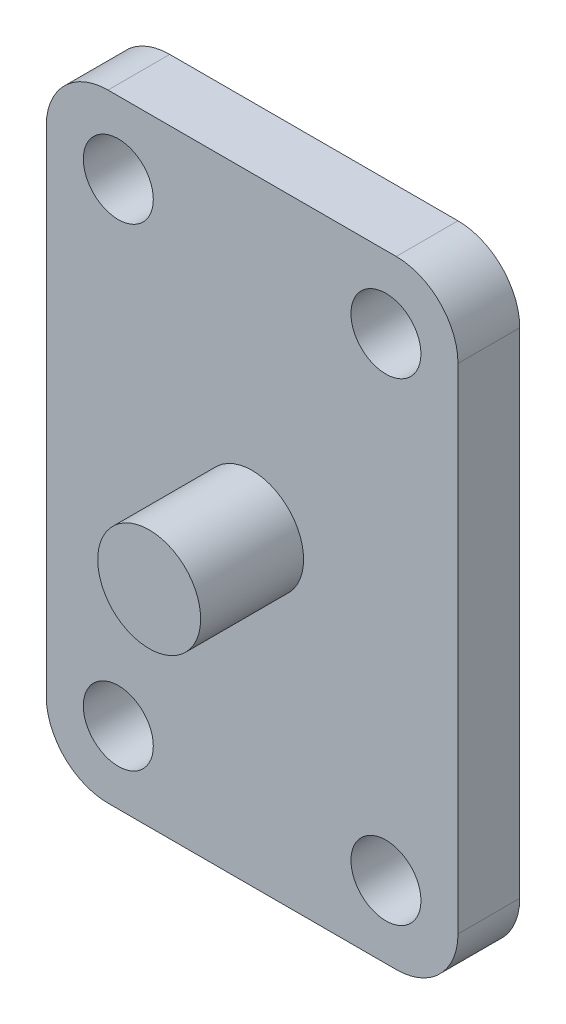
SolidWorks part; units mm, degrees
ref_plane "Front Plane" through (0, 0, 0) normal (0, 0, 1) x (1, 0, 0)
ref_plane "Top Plane" through (0, 0, 0) normal (0, 1, 0) x (1, 0, 0)
ref_plane "Right Plane" through (0, 0, 0) normal (1, 0, 0) x (0, 0, -1)
sketch "Sketch1" plane through (0, 0, 0) normal (0, 0, 1) x (1, 0, 0)
  line L1 (-10, -15) -> (10, -15)
  line L2 (-10, -15) -> (-10, 15)
  line L3 (-10, 15) -> (10, 15)
  line L4 (10, -15) -> (10, 15)
  line L5 (-10, -15) -> (10, 15) construction
  line L6 (-10, 15) -> (10, -15) construction
  point P0 (0, 0)
  dimension "D1" = 30
  dimension "D2" = 20
extrude "Boss-Extrude1" add sketch "Sketch1" along normal blind 3
sketch "Sketch2" plane through (0, 0, 3) normal (0, 0, 1) x (1, 0, 0)
  ellipse E0 centre (0, 0) end of major axis (0, 10) minor radius 5
  ellipse E1 centre (0, 0) end of major axis (0, 9) minor radius 4
  dimension "D1" = 5
  dimension "D2" = 10
  dimension "D3" = 4
  dimension "D4" = 9
extrude "Boss-Extrude2" [suppressed] add sketch "Sketch2" along normal blind 13
hole_wizard "Ø3.4 (3.4) Diameter Hole1" positions "Sketch4" profile "Sketch3" hole size "Ø3.4" standard "ANSI Metric" end condition through all
sketch "Sketch4" plane through (0, 0, 3) normal (0, 0, 1) x (1, 0, 0)
  line L0 (-10, 15) -> (-10, -15) construction
  line L1 (10, 15) -> (-10, 15) construction
  line L2 (10, -15) -> (10, 15) construction
  line L3 (-10, -15) -> (10, -15) construction
  point P0 (-6.5, 11.5)
  point P2 (6.5, 11.5)
  point P4 (6.5, -11.5)
  point P6 (-6.5, -11.5)
  dimension "D1" = 3.5
  dimension "D2" = 3.5
  dimension "D3" = 3.5
  dimension "D4" = 3.5
  dimension "D5" = 3.5
  dimension "D6" = 3.5
  dimension "D7" = 3.5
  dimension "D8" = 3.5
sketch "Sketch3" plane through (-6.5, 11.5, 3) normal (1, 0, 0) x (0, -1, 0)
  line L0 (0, 0) -> (0, 3)
  line L1 (0, 3) -> (1.7, 3)
  line L2 (1.7, 3) -> (1.7, 0)
  line L5 (1.7, 0) -> (0, 0)
  line L11 (0, -6.35) -> (0, 107.95) construction
  dimension "Thru Hole Dia." = 3.4
  dimension "Thru Hole Depth" = 3
sketch "Sketch5" plane through (0, 0, 0) normal (0, 0, -1) x (-1, 0, 0)
  circle A0 centre (0, 0) radius 3.4
extrude "Cut-Extrude1" cut sketch "Sketch5" against normal blind 0.5
fillet "Fillet1" radius 3 4 edges at (-10, -15, 1.5) (10, -15, 1.5) (10, 15, 1.5) (-10, 15, 1.5)
sketch "Sketch7" plane through (0, 0, 3) normal (0, 0, 1) x (1, 0, 0)
  line L1 (4, -7.5) -> (-4, -7.5)
  line L2 (4, -7.5) -> (4, 7.5)
  line L3 (4, 7.5) -> (-4, 7.5)
  line L4 (-4, -7.5) -> (-4, 7.5)
  line L5 (4, -7.5) -> (-4, 7.5) construction
  line L6 (4, 7.5) -> (-4, -7.5) construction
  point P0 (0, 0)
  dimension "D1" = 8
  dimension "D2" = 15
extrude "Boss-Extrude3" add sketch "Sketch7" along normal blind 11
sketch "Sketch8" plane through (4, 0, 0) normal (1, 0, 0) x (0, 0, -1)
  line L0 (-14, -7.5) -> (-14, -7) construction
  line L1 (-14, -7.5) -> (-14, 7.5) construction
  line L2 (-14, -7) -> (-13.134, -7.5)
  line L3 (-14, -7.5) -> (-3, -7.5) construction
  line L4 (-13.134, -7.5) -> (-13.134, 7.5) construction
  line L5 (-14, 7.5) -> (-3, 7.5) construction
  line L6 (-14, -7) -> (-13.134, -6.5)
  line L7 (-14, -6) -> (-13.134, -6.5)
  line L8 (-14, -6) -> (-13.134, -5.5)
  line L9 (-14, -5) -> (-13.134, -5.5)
  line L10 (-14, -5) -> (-13.134, -4.5)
  line L11 (-14, -4) -> (-13.134, -4.5)
  line L12 (-14, -4) -> (-13.134, -3.5)
  line L13 (-14, -3) -> (-13.134, -3.5)
  line L14 (-14, -3) -> (-13.134, -2.5)
  line L15 (-14, -2) -> (-13.134, -2.5)
  line L16 (-14, -2) -> (-13.134, -1.5)
  line L17 (-14, -1) -> (-13.134, -1.5)
  line L18 (-14, -1) -> (-13.134, -0.5)
  line L19 (-14, 0) -> (-13.134, -0.5)
  line L20 (-14, 0) -> (-13.134, 0.5)
  line L21 (-14, 1) -> (-13.134, 0.5)
  line L22 (-14, 1) -> (-13.134, 1.5)
  line L23 (-14, 2) -> (-13.134, 1.5)
  line L24 (-14, 2) -> (-13.134, 2.5)
  line L25 (-14, 3) -> (-13.134, 2.5)
  line L26 (-14, 3) -> (-13.134, 3.5)
  line L27 (-14, 4) -> (-13.134, 3.5)
  line L28 (-14, 4) -> (-13.134, 4.5)
  line L29 (-14, 5) -> (-13.134, 4.5)
  line L30 (-14, 5) -> (-13.134, 5.5)
  line L31 (-14, 6) -> (-13.134, 5.5)
  line L32 (-14, 6) -> (-13.134, 6.5)
  line L33 (-14, 7) -> (-13.134, 6.5)
  line L34 (-14, 7) -> (-13.134, 7.5)
  dimension "D1" = 0.5
  dimension "D2" = 60
  dimension "D3" = 60
  dimension "D4" = 15
extrude "Cut-Extrude3" cut sketch "Sketch8" against normal through all and the other way through all
sketch "Sketch11" plane through (0, 0, 3) normal (0, 0, 1) x (1, 0, 0)
  circle A0 centre (0, 0) radius 2.5
  dimension "D1" = 5
extrude "Cut-Extrude4" cut sketch "Sketch11" along normal through all flip side to cut
sketch "Sketch12" plane through (10, 0, 0) normal (1, 0, 0) x (0, 0, -1)
  line L1 (-3, -12) -> (-3, 12) construction
  line L2 (-15.4302, 10.4417) -> (-8, 10.4417)
  line L3 (-15.4302, 10.4417) -> (-15.4302, -10.6669)
  line L4 (-15.4302, -10.6669) -> (-8, -10.6669)
  line L5 (-8, 10.4417) -> (-8, -10.6669)
  dimension "D1" = 5
extrude "Cut-Extrude5" cut sketch "Sketch12" against normal through all
sketch "Sketch13" plane through (0, 0, 0) normal (0, 0, -1) x (-1, 0, 0)
  circle A0 centre (0, 0) radius 2.75
  circle A1 centre (0, 0) radius 3.4
  dimension "D1" = 5.5
extrude "Boss-Extrude4" add sketch "Sketch13" against normal up to surface (0.5 mm away) up to face at (-3.4, 0, 0.5)
